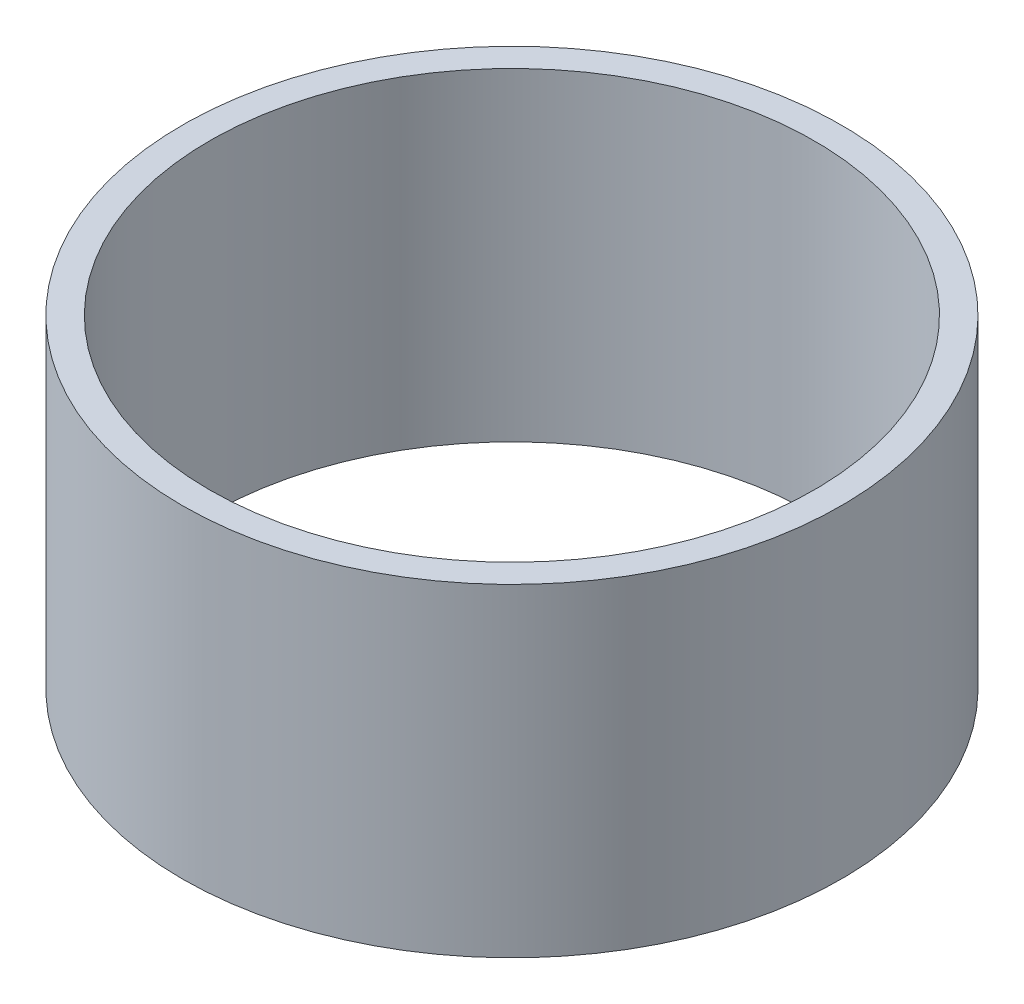
SolidWorks part; units mm, degrees
ref_plane "Front Plane" through (0, 0, 0) normal (0, 0, 1) x (1, 0, 0)
ref_plane "Top Plane" through (0, 0, 0) normal (0, 1, 0) x (1, 0, 0)
ref_plane "Right Plane" through (0, 0, 0) normal (1, 0, 0) x (0, 0, -1)
sketch "Sketch1" plane through (0, 0, 0) normal (0, 1, 0) x (1, 0, 0)
  circle A0 centre (0, 0) radius 13.9065
  circle A1 centre (0, 0) radius 15.1576
  dimension "D1" = 27.813
  dimension "D2" = 30.3152
extrude "Boss-Extrude1" add sketch "Sketch1" along normal blind 14.8717
